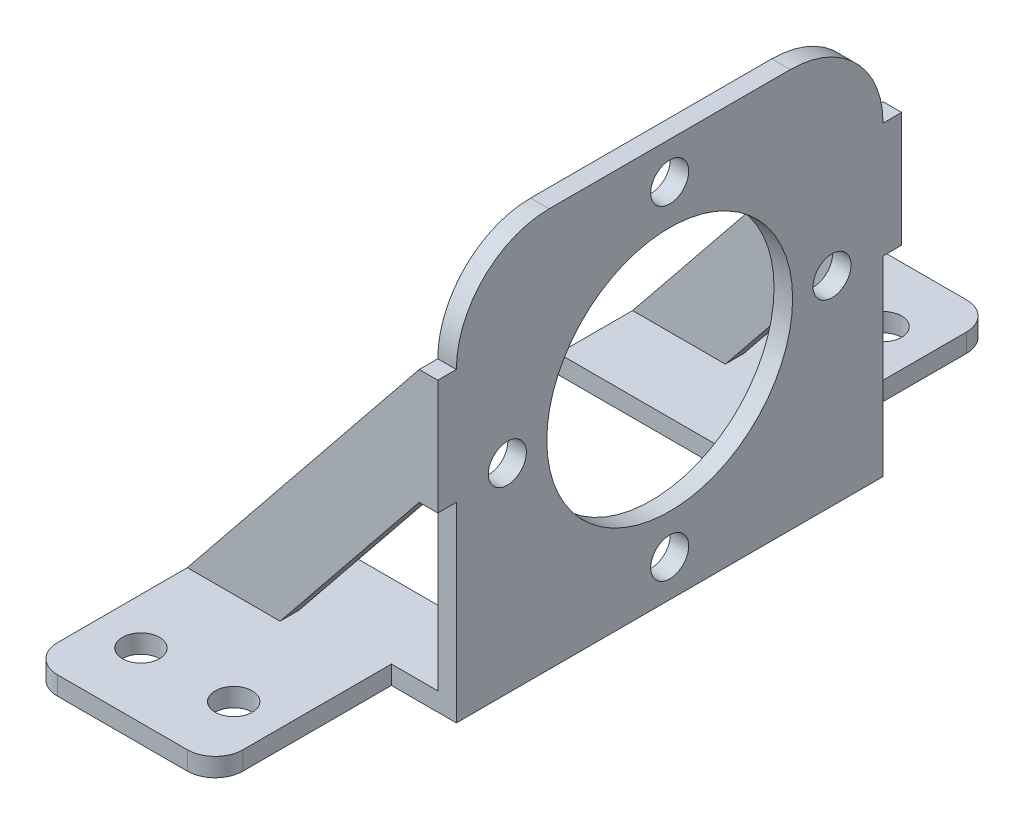
SolidWorks part; units mm, degrees
material "AISI 304"
ref_plane "Front Plane" through (0, 0, 0) normal (0, 0, 1) x (1, 0, 0)
ref_plane "Top Plane" through (0, 0, 0) normal (0, 1, 0) x (1, 0, 0)
ref_plane "Right Plane" through (0, 0, 0) normal (1, 0, 0) x (0, 0, -1)
sketch "Sketch1" plane through (0, 0, 0) normal (1, 0, 0) x (0, 0, -1)
  line L0 (0, 30.6219) -> (0, -32.2275) construction
  line L1 (-35.7829, 0) -> (47.3282, 0) construction
  line L3 (-13, 21.5) -> (13, 21.5)
  line L4 (-23, 11.5) -> (-23, -21.5)
  line L5 (-23, -21.5) -> (23, -21.5)
  line L6 (23, 11.5) -> (23, -21.5)
  line L7 (-23, 21.5) -> (23, -21.5) construction
  line L8 (-23, -21.5) -> (23, 21.5) construction
  circle A1 centre (0, 0) radius 17.5 construction
  circle A2 centre (0, 0) radius 13.25
  circle A3 centre (0, 17.5) radius 2.05
  circle A4 centre (17.5, 0) radius 2.05
  circle A5 centre (0, -17.5) radius 2.05
  circle A6 centre (-17.5, 0) radius 2.05
  arc A7 (13, 21.5) -> (23, 11.5) centre (13, 11.5) cw
  arc A8 (-13, 21.5) -> (-23, 11.5) centre (-13, 11.5) ccw
  dimension "D1" = 10
  dimension "D2" = 35
  dimension "D3" = 26.5
  dimension "D4" = 4.1
  dimension "D5" = 4.1
  dimension "D6" = 4.1
  dimension "D7" = 4.1
  dimension "D8" = 46
  dimension "D9" = 43
extrude "Boss-Extrude1" add sketch "Sketch1" along normal blind 2
sketch "Sketch2" plane through (0, -21.5, 0) normal (0, -1, 0) x (1, 0, 0)
  line L0 (-15.1458, 0) -> (14.7805, 0) construction
  line L1 (-5, 23) -> (-25, 23)
  line L2 (-25, 23) -> (-25, 47)
  line L3 (-25, 47) -> (-5, 47)
  line L4 (-5, 47) -> (-5, 28)
  line L5 (0, 23) -> (-31.2254, 23) construction
  line L6 (0, 23) -> (0, -23) construction
  line L7 (-25, 35) -> (-5, 35) construction
  line L8 (-15, 47) -> (-15, 23) construction
  line L9 (-15, -47) -> (-15, -23) construction
  line L10 (-25, -35) -> (-5, -35) construction
  line L15 (-5, 28) -> (2, 28)
  line L16 (2, 28) -> (2, 23)
  line L17 (2, 23) -> (-5, 23)
  line L18 (2, -23) -> (-5, -23)
  line L19 (2, -28) -> (2, -23)
  line L20 (-5, -28) -> (2, -28)
  line L21 (-5, -47) -> (-5, -28)
  line L22 (-25, -47) -> (-5, -47)
  line L23 (-25, -23) -> (-25, -47)
  line L24 (-5, -23) -> (-25, -23)
  circle A0 centre (-20, 35) radius 2
  circle A1 centre (-10, 35) radius 2
  circle A4 centre (-10, -35) radius 2
  circle A5 centre (-20, -35) radius 2
  dimension "D3" = 4
  dimension "D1" = 5
  dimension "D2" = 20
  dimension "D4" = 5
  dimension "D5" = 70
  dimension "D6" = 5
extrude "Boss-Extrude2" add sketch "Sketch2" against normal blind 2
sketch "Sketch3" plane through (0, 0, -23) normal (0, 0, -1) x (-1, 0, 0)
  line L0 (-2, 11.5) -> (0, 11.5)
  line L1 (0, 11.5) -> (25, -19.5)
  line L2 (25, -19.5) -> (15, -19.5)
  line L3 (25, -19.5) -> (5, -19.5) construction
  line L4 (15, -19.5) -> (0, -0.9)
  line L5 (0, -19.5) -> (0, 11.5) construction
  line L6 (0, -0.9) -> (-2, -0.9)
  line L7 (-2, -19.5) -> (-2, 11.5) construction
  line L8 (-2, -0.9) -> (-2, 11.5)
extrude "Boss-Extrude3" add sketch "Sketch3" along normal blind 2
sketch "Sketch4" plane through (0, 0, 23) normal (0, 0, 1) x (1, 0, 0)
  line L0 (2, 11.5) -> (0, 11.5)
  line L1 (0, 11.5) -> (-25, -19.5)
  line L2 (-25, -19.5) -> (-15, -19.5)
  line L3 (-15, -19.5) -> (0, -0.9)
  line L4 (0, -0.9) -> (2, -0.9)
  line L5 (2, -0.9) -> (2, 11.5)
extrude "Boss-Extrude4" add sketch "Sketch4" along normal blind 2
sketch "Sketch5" plane through (0, -21.5, 0) normal (0, -1, 0) x (1, 0, 0)
  line L0 (-5, 28) -> (-5, 23)
  line L1 (-25, 23) -> (0, 23) construction
  line L2 (-5, 23) -> (2, 23)
  line L3 (2, 23) -> (2, 28)
  line L4 (2, 28) -> (-5, 28)
  line L5 (-7.9763, 0) -> (6.4511, 0) construction
  line L6 (2, -23) -> (2, -28)
  line L7 (-5, -23) -> (2, -23)
  line L8 (-5, -28) -> (-5, -23)
  line L9 (2, -28) -> (-5, -28)
extrude "Cut-Extrude1" cut sketch "Sketch5" against normal blind 2
sketch "Sketch6" plane through (0, -19.5, 0) normal (0, 1, 0) x (1, 0, 0)
  line L0 (-25, 47) -> (-25, 42)
  line L1 (-25, 25) -> (-25, 47) construction
  line L2 (-25, 42) -> (-5, 42)
  line L3 (-5, 47) -> (-5, 23) construction
  line L4 (-5, 42) -> (-5, 47)
  line L5 (-5, 47) -> (-25, 47)
  line L6 (-29.5733, 0) -> (8.178, 0) construction
  line L7 (-5, -42) -> (-5, -47)
  line L8 (-25, -42) -> (-5, -42)
  line L9 (-25, -47) -> (-25, -42)
  line L10 (-5, -47) -> (-25, -47)
  dimension "D1" = 5
extrude "Cut-Extrude2" cut sketch "Sketch6" against normal blind 2
fillet "Fillet1" radius 3 4 edges at (-5, -20.5, 42) (-25, -20.5, 42) (-25, -20.5, -42) (-5, -20.5, -42)
sketch "Sketch8" plane through (0, -21.5, 0) normal (0, -1, 0) x (1, 0, 0)
  line L0 (-25, 23) -> (-25, 15)
  line L1 (-25, 15) -> (0, 15)
  line L2 (0, 23) -> (0, -23) construction
  line L3 (0, 15) -> (0, 23)
  line L4 (0, 23) -> (-25, 23)
  line L5 (-34.6469, 0) -> (7.2683, 0) construction
  line L6 (0, -15) -> (0, -23)
  line L7 (-25, -15) -> (0, -15)
  line L8 (-25, -23) -> (-25, -15)
  line L9 (0, -23) -> (-25, -23)
  dimension "D1" = 8
extrude "Boss-Extrude5" add sketch "Sketch8" against normal blind 2
